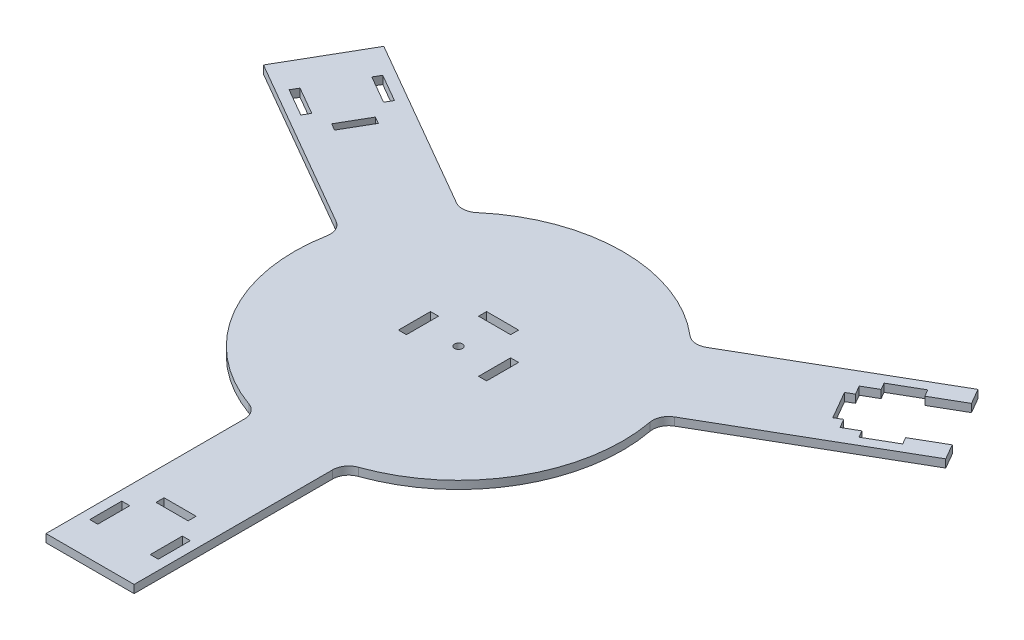
SolidWorks part; units mm, degrees
ref_plane "Front Plane" through (0, 0, 0) normal (0, 0, 1) x (1, 0, 0)
ref_plane "Top Plane" through (0, 0, 0) normal (0, 1, 0) x (1, 0, 0)
ref_plane "Right Plane" through (0, 0, 0) normal (1, 0, 0) x (0, 0, -1)
sketch "Sketch1" plane through (0, 0, 0) normal (0, 1, 0) x (1, 0, 0)
  line L0 (0, 0) -> (0, -292.1) construction
  line L1 (-34.925, -292.1) -> (34.925, -292.1)
  line L2 (-34.925, -292.1) -> (-34.925, -134.7038)
  line L3 (34.925, -292.1) -> (34.925, -134.7038)
  line L4 (-235.5035, 176.2959) -> (-99.1944, 97.5979)
  line L5 (-235.5035, 176.2959) -> (-270.4285, 115.8041)
  line L6 (-270.4285, 115.8041) -> (-134.1194, 37.106)
  line L7 (0, 0) -> (-252.966, 146.05) construction
  line L8 (270.4285, 115.8041) -> (134.1194, 37.106)
  line L9 (270.4285, 115.8041) -> (263.38, 128.0124)
  line L10 (235.5035, 176.2959) -> (99.1944, 97.5979)
  line L11 (0, 0) -> (252.966, 146.05) construction
  line L12 (196.4588, 153.7534) -> (231.3838, 93.2616) construction
  line L13 (202.8936, 102.476) -> (206.9576, 95.4369)
  line L14 (190.1936, 124.473) -> (184.6943, 121.298)
  line L15 (184.6943, 121.298) -> (197.3943, 99.301)
  line L16 (197.3943, 99.301) -> (202.8936, 102.476)
  line L17 (206.9576, 95.4369) -> (217.9561, 101.7869)
  line L18 (186.5106, 130.8522) -> (221.2659, 150.9182) construction
  line L19 (206.5766, 96.0968) -> (241.3319, 116.1628) construction
  line L20 (241.3319, 116.1628) -> (221.2659, 150.9182) construction
  line L21 (186.5106, 130.8522) -> (206.5766, 96.0968) construction
  line L22 (193.9531, 143.3613) -> (215.9502, 156.0613)
  line L23 (193.9531, 143.3613) -> (197.1281, 137.8621)
  line L24 (239.9532, 114.4869) -> (263.38, 128.0124)
  line L25 (219.1252, 150.5621) -> (215.9502, 156.0613)
  line L26 (239.9532, 114.4869) -> (243.1282, 108.9877)
  line L27 (219.1252, 150.5621) -> (242.552, 164.0876)
  line L28 (221.1311, 96.2877) -> (217.9561, 101.7869)
  line L29 (221.1311, 96.2877) -> (243.1282, 108.9877)
  line L30 (190.1936, 124.473) -> (186.1296, 131.5121)
  line L31 (197.1281, 137.8621) -> (186.1296, 131.5121)
  line L32 (242.552, 164.0876) -> (235.5035, 176.2959)
  line L33 (12.7, -220.726) -> (-12.7, -220.726)
  line L34 (12.7, -227.076) -> (12.7, -220.726)
  line L35 (-12.7, -220.726) -> (-12.7, -227.076)
  line L36 (-27.178, -239.776) -> (-20.828, -239.776)
  line L37 (-27.178, -239.776) -> (-27.178, -265.176)
  line L38 (-20.828, -265.176) -> (-27.178, -265.176)
  line L39 (20.828, -265.176) -> (27.178, -265.176)
  line L40 (27.178, -239.776) -> (27.178, -265.176)
  line L41 (27.178, -239.776) -> (20.828, -239.776)
  line L42 (-197.5043, 99.2375) -> (-184.8043, 121.2345)
  line L43 (-203.0036, 102.4125) -> (-197.5043, 99.2375)
  line L44 (-184.8043, 121.2345) -> (-190.3036, 124.4095)
  line L45 (-194.0631, 143.2978) -> (-197.2381, 137.7986)
  line L46 (-194.0631, 143.2978) -> (-216.0602, 155.9978)
  line L47 (-219.2352, 150.4986) -> (-216.0602, 155.9978)
  line L48 (-240.0632, 114.4234) -> (-243.2382, 108.9242)
  line L49 (-221.2411, 96.2242) -> (-243.2382, 108.9242)
  line L50 (-221.2411, 96.2242) -> (-218.0661, 101.7234)
  line L51 (-12.7, -227.076) -> (12.7, -227.076)
  line L52 (20.828, -265.176) -> (20.828, -239.776)
  line L53 (-20.828, -265.176) -> (-20.828, -239.776)
  line L54 (-203.0036, 102.4125) -> (-190.3036, 124.4095)
  line L55 (-197.2381, 137.7986) -> (-219.2352, 150.4986)
  line L56 (-218.0661, 101.7234) -> (-240.0632, 114.4234)
  arc A0 (-43.3917, -122.7302) -> (-127.9833, 23.7868) centre (0, 0) cw
  arc A1 (-84.5916, 98.9434) -> (84.5916, 98.9434) centre (0, 0) cw
  arc A2 (127.9833, 23.7868) -> (43.3917, -122.7302) centre (0, 0) cw
  arc A3 (-127.9833, 23.7868) -> (-134.1194, 37.106) centre (-140.4694, 26.1075) ccw
  arc A4 (-84.5916, 98.9434) -> (-99.1944, 97.5979) centre (-92.8444, 108.5964) cw
  arc A5 (-43.3917, -122.7302) -> (-34.925, -134.7038) centre (-47.625, -134.7038) cw
  arc A6 (43.3917, -122.7302) -> (34.925, -134.7038) centre (47.625, -134.7038) ccw
  arc A7 (134.1194, 37.106) -> (127.9833, 23.7868) centre (140.4694, 26.1075) ccw
  arc A8 (84.5916, 98.9434) -> (99.1944, 97.5979) centre (92.8444, 108.5964) ccw
  circle A9 centre (0, 0) radius 292.1 construction
  circle A10 centre (213.9213, 123.5075) radius 2.9337 construction
  circle A11 centre (0, 0) radius 220.726 construction
  circle A12 centre (0, 0) radius 3.175
  point P6 (0, -292.1)
  point P36 (0, -220.726)
  point P38 (191.0443, 110.2995)
  point P44 (203.8883, 140.8852)
  dimension "D1" = 130.175
  dimension "D4" = 12.7
  dimension "D6" = 5.8674
  dimension "D15" = 441.452
  dimension "D16" = 6.35
  dimension "D2" = 292.1
  dimension "D3" = 69.85
  dimension "D5" = 247.015
  dimension "D7" = 12.7
  dimension "D8" = 6.35
  dimension "D9" = 25.4
  dimension "D10" = 40.132
  dimension "D11" = 40.132
  dimension "D12" = 25.4
  dimension "D13" = 6.35
  dimension "D14" = 54.356
extrude "Extrude2" add sketch "Sketch1" along normal blind 6.35
sketch "Sketch2" plane through (0, 6.35, 0) normal (0, 1, 0) x (1, 0, 0)
  line L0 (-31.75, 12.7) -> (-31.75, -12.7) construction
  line L1 (-34.925, 12.7) -> (-28.575, 12.7)
  line L2 (-34.925, 12.7) -> (-34.925, -12.7)
  line L3 (-34.925, -12.7) -> (-28.575, -12.7)
  line L4 (-28.575, 12.7) -> (-28.575, -12.7)
  line L5 (12.7, 28.575) -> (-12.7, 28.575)
  line L6 (12.7, 34.925) -> (12.7, 28.575)
  line L7 (12.7, 34.925) -> (-12.7, 34.925)
  line L8 (-12.7, 34.925) -> (-12.7, 28.575)
  line L9 (0, 0) -> (-31.75, 0) construction
  line L10 (0, 0) -> (0, 31.75) construction
  line L11 (12.7, 31.75) -> (-12.7, 31.75) construction
  line L12 (28.575, -12.7) -> (28.575, 12.7)
  line L13 (34.925, -12.7) -> (28.575, -12.7)
  line L14 (34.925, -12.7) -> (34.925, 12.7)
  line L15 (34.925, 12.7) -> (28.575, 12.7)
  line L16 (0, 0) -> (31.75, 0) construction
  line L17 (31.75, -12.7) -> (31.75, 12.7) construction
  line L24 (-31.75, 12.7) -> (-31.75, 31.75) construction
  line L25 (-31.75, 31.75) -> (-12.7, 31.75) construction
  line L29 (-12.7, -34.925) -> (12.7, -34.925) [skipped]
  line L30 (12.7, -34.925) -> (12.7, -28.575) [skipped]
  line L31 (-12.7, -28.575) -> (12.7, -28.575) [skipped]
  line L32 (0, 0) -> (0, -31.75) construction
  line L33 (-12.7, -31.75) -> (12.7, -31.75) construction
  line L34 (-12.7, -34.925) -> (-12.7, -28.575) [skipped]
  circle A0 centre (0, 0) radius 60.325 construction
  circle A1 centre (0, 0) radius 31.75 construction
  point P9 (-31.75, 0)
  dimension "D1" = 120.65
  dimension "D4" = 63.5
  dimension "D2" = 6.35
  dimension "D3" = 25.4
extrude "Extrude4" cut sketch "Sketch2" against normal through all
